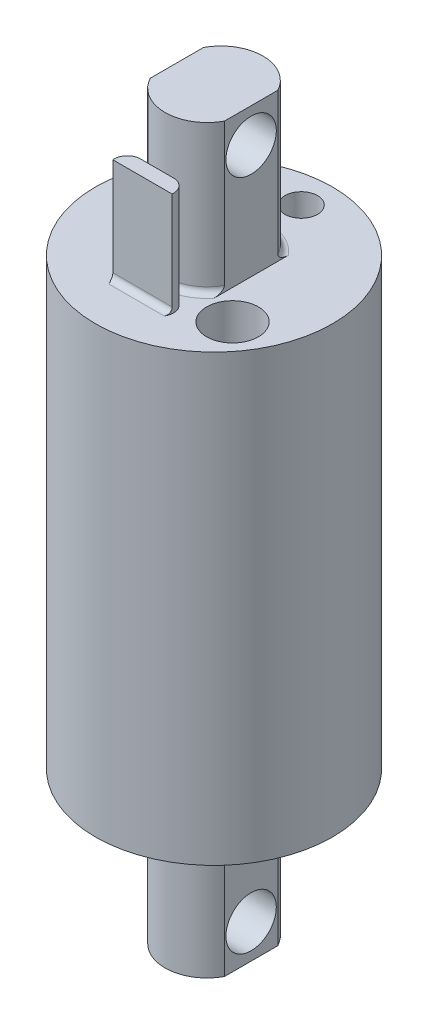
SolidWorks part; units mm, degrees
ref_plane "Front Plane" through (0, 0, 0) normal (0, 0, 1) x (1, 0, 0)
ref_plane "Top Plane" through (0, 0, 0) normal (0, 1, 0) x (1, 0, 0)
ref_plane "Right Plane" through (0, 0, 0) normal (1, 0, 0) x (0, 0, -1)
sketch "Sketch2" plane through (0, 0, 0) normal (0, 1, 0) x (1, 0, 0)
  circle A0 centre (0, 0) radius 8
  dimension "D1" = 16
extrude "Boss-Extrude1" add sketch "Sketch2" along normal blind 30
sketch "Sketch4" plane through (0, 30, 0) normal (0, 1, 0) x (1, 0, 0)
  line L1 (-55, 0) -> (55, 0) construction
  line L2 (2.5045, -1.8) -> (2.5045, 1.8)
  line L5 (0, -55) -> (0, 55) construction
  line L6 (-2.5045, -1.8) -> (-2.5045, 1.8)
  arc A2 (-2.5045, 1.8) -> (2.5045, 1.8) centre (0, 0.4642) cw
  arc A3 (-2.5045, -1.8) -> (2.5045, -1.8) centre (0, -0.4642) ccw
  point P5 (2.5045, 0)
  point P8 (1.2, 0)
  dimension "D1" = 1.8
  dimension "D2" = 5.009
extrude "Boss-Extrude3" add sketch "Sketch4" along normal blind 10
sketch "Sketch8" plane through (0, 30, 0) normal (0, 1, 0) x (1, 0, 0)
  line L3 (-1.2, -3.844) -> (1.2, -3.844)
  line L4 (-2, -4.8267) -> (2, -4.8267)
  line L5 (0, -55) -> (0, 55) construction
  arc A4 (1.2, -3.844) -> (2, -4.8267) centre (1.1087, -4.7354) cw
  arc A5 (-1.2, -3.844) -> (-2, -4.8267) centre (-1.1087, -4.7354) ccw
  point P8 (0, -4.8267)
  point P9 (0, -3.844)
  dimension "D1" = 2
  dimension "D2" = 1.2
extrude "Boss-Extrude4" add sketch "Sketch8" along normal blind 7
fillet "Fillet1" radius 0.4 3 edges at (0, 30, -3.3027) (0, 30, 3.3027) (0, 30, 4.8267)
sketch "Sketch12" plane through (0, 0, 0) normal (0, 1, 0) x (1, 0, 0)
  circle A1 centre (0, 5.8879) radius 1.1
  circle A2 centre (4.5113, -3.2605) radius 1.75
  point P2 (0, 0)
  point P3 (0, 0)
  point P4 (4.5113, -3.2605)
  point P5 (0, 5.8879)
  dimension "D1" = 3.5
  dimension "D2" = 2.2
extrude "Cut-Extrude2" cut sketch "Sketch12" along normal through all
ref_plane "Plane1" through (0, 15, 0) normal (0, 1, 0) x (1, 0, 0)
sketch "Sketch13" plane through (-2.5045, 0, 0) normal (-1, 0, 0) x (0, 0, 1)
  circle A0 centre (0, 37.692) radius 1.7
  dimension "D1" = 3.4
extrude "Cut-Extrude3" cut sketch "Sketch13" against normal through all
mirror "Mirror1" about plane through (0, 15, 0) normal (0, 1, 0) of "Cut-Extrude3", "Boss-Extrude3"
sketch "Sketch14" plane through (0, 30, 0) normal (0, 1, 0) x (1, 0, 0)
  circle A0 centre (4.2242, -4.1422) radius 1.75
  dimension "D1" = 3.5
sketch "Sketch15" plane through (0, 0, 0) normal (0, 0, 1) x (1, 0, 0)
  line L0 (0, -8.8) -> (0, 8.8) construction
  circle A0 centre (0, 16.3648) radius 0.5
  dimension "D1" = 1
